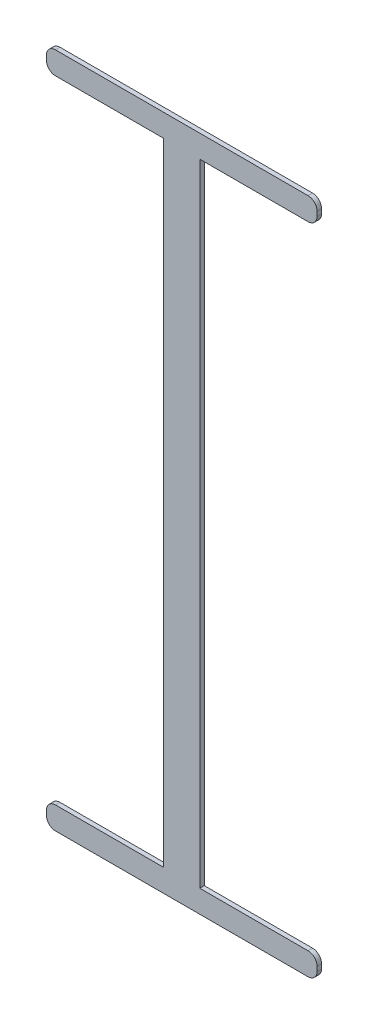
SolidWorks part; units mm, degrees
ref_plane "前视基准面" through (0, 0, 0) normal (0, 0, 1) x (1, 0, 0)
ref_plane "上视基准面" through (0, 0, 0) normal (0, 1, 0) x (1, 0, 0)
ref_plane "右视基准面" through (0, 0, 0) normal (1, 0, 0) x (0, 0, -1)
sketch "草图1" plane through (0, 0, 0) normal (0, 0, 1) x (1, 0, 0)
  line L0 (-56, 150) -> (56, 150)
  line L1 (60, 146) -> (60, 144)
  line L2 (56, 140) -> (8, 140)
  line L3 (8, 140) -> (8, -140)
  line L4 (0, -55) -> (0, 55) construction
  line L5 (-8, 140) -> (-8, -140)
  line L6 (-56, 140) -> (-8, 140)
  line L7 (-60, 146) -> (-60, 144)
  line L8 (55, 0) -> (-55, 0) construction
  line L9 (-60, -146) -> (-60, -144)
  line L10 (-56, -140) -> (-8, -140)
  line L11 (56, -140) -> (8, -140)
  line L12 (60, -146) -> (60, -144)
  line L13 (-56, -150) -> (56, -150)
  arc A0 (60, 146) -> (56, 150) centre (56, 146) ccw
  arc A1 (56, 140) -> (60, 144) centre (56, 144) ccw
  arc A2 (-56, 140) -> (-60, 144) centre (-56, 144) cw
  arc A3 (-60, 146) -> (-56, 150) centre (-56, 146) cw
  arc A4 (-60, -146) -> (-56, -150) centre (-56, -146) ccw
  arc A5 (-56, -140) -> (-60, -144) centre (-56, -144) ccw
  arc A6 (56, -140) -> (60, -144) centre (56, -144) cw
  arc A7 (60, -146) -> (56, -150) centre (56, -146) cw
  point P4 (0, 0)
  point P5 (0, -150)
  point P6 (0, 0)
  point P22 (0, 150)
  point P37 (-8, 0)
  point P38 (8, 0)
  dimension "D5" = 4
  dimension "D1" = 150
  dimension "D2" = 10
  dimension "D3" = 60
  dimension "D4" = 8
extrude "凸台-拉伸1" add sketch "草图1" along normal blind 2
